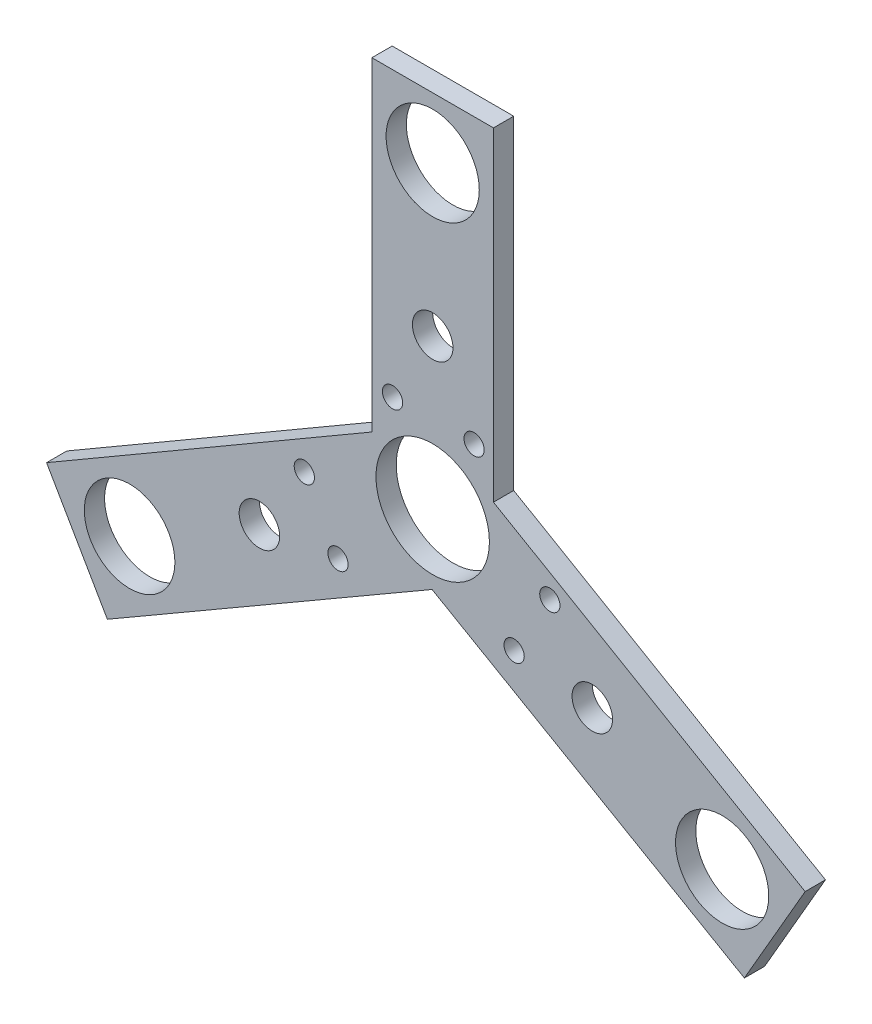
SolidWorks part; units mm, degrees
material "Plain Carbon Steel"
ref_plane "Front Plane" through (0, 0, 0) normal (0, 0, 1) x (1, 0, 0)
ref_plane "Top Plane" through (0, 0, 0) normal (0, 1, 0) x (1, 0, 0)
ref_plane "Right Plane" through (0, 0, 0) normal (1, 0, 0) x (0, 0, -1)
sketch "Sketch1" plane through (0, 0, 0) normal (0, 0, 1) x (1, 0, 0)
  line L0 (0, 0) -> (0, 200.269) construction
  line L1 (0, 0) -> (173.8456, -100.3698) construction
  line L2 (0, 0) -> (-174.6368, -100.8266) construction
  line L3 (-30, 178) -> (30, 178)
  line L4 (183.8575, -71.5091) -> (153.8575, -123.4707)
  line L5 (-190.5837, -75.3925) -> (-160.5837, -127.3541)
  line L6 (30, 178) -> (30, 18)
  line L7 (-30, 178) -> (-30, 18)
  line L8 (183.8575, -71.5091) -> (30, 18)
  line L9 (153.8575, -123.4707) -> (-0.2951, -34.4707)
  line L10 (-190.5837, -75.3925) -> (-30, 18)
  line L11 (-160.5837, -127.3541) -> (-0.2951, -34.4707)
  circle A0 centre (0, 0) radius 28
  circle A1 centre (0, 148) radius 23
  circle A2 centre (-149.6029, -86.3733) radius 22.3569
  circle A3 centre (142.8767, -82.4899) radius 23
  circle A4 centre (0, 74) radius 10
  circle A5 centre (-85.5171, -49.3733) radius 10
  circle A6 centre (78.7908, -45.4899) radius 10
  dimension "D3" = 56
  dimension "D18" = 46
  dimension "D19" = 44.7138
  dimension "D21" = 46
  dimension "D24" = 20
  dimension "D25" = 20
  dimension "D26" = 20
  dimension "D1" = 120
  dimension "D2" = 120
  dimension "D4" = 60
  dimension "D5" = 30
  dimension "D6" = 178
  dimension "D7" = 60
  dimension "D8" = 30
  dimension "D9" = 60
  dimension "D10" = 30
  dimension "D11" = 160
  dimension "D12" = 160
  dimension "D13" = 178
  dimension "D14" = 178
  dimension "D15" = 185.7668
  dimension "D16" = 185.256
  dimension "D17" = 30
  dimension "D20" = 30
  dimension "D22" = 30
  dimension "D23" = 104
  dimension "D27" = 104
  dimension "D28" = 104
sketch "Sketch3" plane through (0, 0, 0) normal (0, 0, 1) x (1, 0, 0)
  line L1 (-190.5837, -75.3925) -> (-160.5837, -127.3541) construction
  line L2 (183.8575, -71.5091) -> (153.8575, -123.4707) construction
  line L3 (-30, 178) -> (30, 178) construction
  circle A0 centre (-63.3542, -15.7606) radius 5
  circle A1 centre (-46.7391, -44.5387) radius 5
  circle A2 centre (40.2011, -40.3293) radius 5
  circle A3 centre (57.836, -9.7846) radius 5
  circle A4 centre (-19.806, 38) radius 5
  circle A5 centre (20.4343, 38) radius 5
  dimension "D7" = 10
  dimension "D8" = 10
  dimension "D9" = 10
  dimension "D10" = 10
  dimension "D11" = 10
  dimension "D12" = 10
  dimension "D1" = 140
  dimension "D2" = 140
  dimension "D3" = 140
  dimension "D4" = 140
  dimension "D5" = 140
  dimension "D6" = 140
sketch "Sketch4" plane through (0, 0, 0) normal (0, 0, 1) x (1, 0, 0)
extrude "Boss-Extrude5" add sketch "Sketch1" against normal blind 10
extrude "Cut-Extrude1" cut sketch "Sketch3" against normal through all
